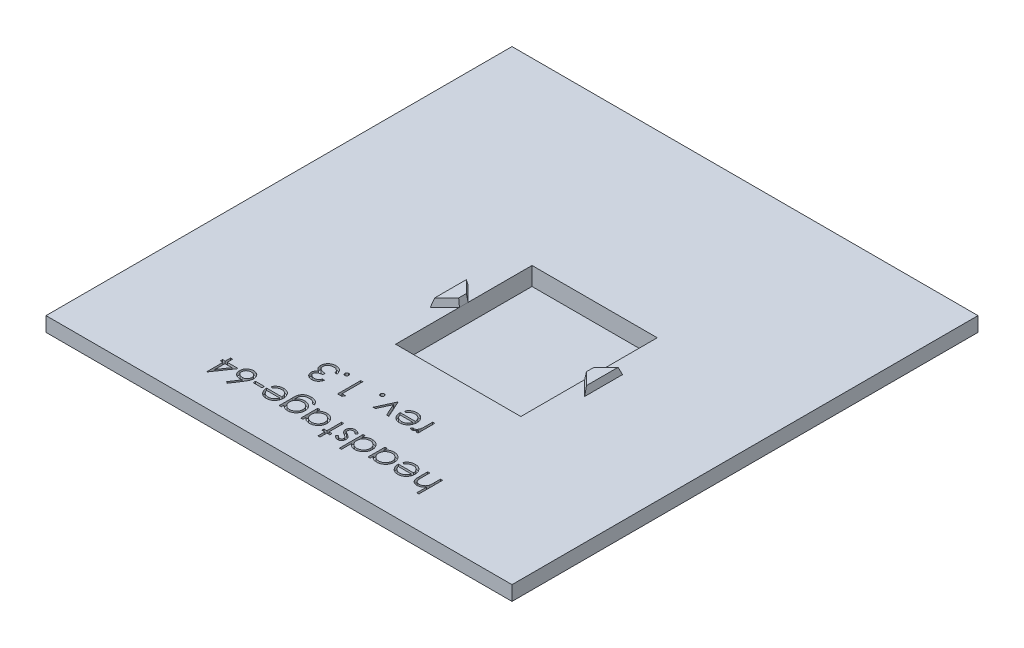
SolidWorks part; units mm, degrees
ref_plane "Front Plane" through (0, 0, 0) normal (0, 0, 1) x (1, 0, 0)
ref_plane "Top Plane" through (0, 0, 0) normal (0, 1, 0) x (1, 0, 0)
ref_plane "Right Plane" through (0, 0, 0) normal (1, 0, 0) x (0, 0, -1)
sketch "Sketch1" plane through (0, 0, 0) normal (0, 1, 0) x (1, 0, 0)
  line L1 (-32, 32) -> (32, 32)
  line L2 (-32, 32) -> (-32, -32)
  line L3 (-32, -32) -> (32, -32)
  line L4 (32, 32) -> (32, -32)
  line L5 (-32, 32) -> (32, -32) construction
  line L6 (-32, -32) -> (32, 32) construction
  point P0 (0, 0)
  dimension "D1" = 64
  dimension "D2" = 64
extrude "Boss-Extrude1" add sketch "Sketch1" along normal blind 4 contours L2 L3 L4 L1
sketch "Sketch2" plane through (0, 0, 0) normal (0, -1, 0) x (1, 0, 0)
  line L1 (-30, 30) -> (30, 30)
  line L2 (-30, 30) -> (-30, -30)
  line L3 (-30, -30) -> (30, -30)
  line L4 (30, 30) -> (30, -30)
  line L5 (-30, 30) -> (30, -30) construction
  line L6 (-30, -30) -> (30, 30) construction
  line L7 (32, 32) -> (-32, 32)
  line L8 (32, 32) -> (32, -32)
  line L9 (32, -32) -> (-32, -32)
  line L10 (-32, 32) -> (-32, -32)
  line L11 (32, 32) -> (-32, -32) construction
  line L12 (32, -32) -> (-32, 32) construction
  point P0 (0, 0)
  point P6 (0, 0)
  line M5 (-32, -32) -> (32, -32)
  line M6 (32, -32) -> (32, 32)
  line M7 (32, 32) -> (-32, 32)
  line M8 (-32, 32) -> (-32, -32)
  dimension "D1" = 2
  dimension "D2" = 2
extrude "Cut-Extrude1" cut sketch "Sketch2" against normal blind 2 contours L1 L4 L3 L2 M8 M5 M6 M7
sketch "Sketch6" plane through (0, 4, 0) normal (0, 1, 0) x (1, 0, 0)
  line L0 (12.61, -2.63) -> (13.4068, -3.4268) construction
  line L4 (12.61, -1.43) -> (12.61, -2.63) construction
  line L5 (12.61, -1.43) -> (13.4068, -0.6332) construction
  line L6 (-4.59, -1.43) -> (-5.3868, -0.6332) construction
  line L7 (-4.59, -2.63) -> (-4.59, -1.43) construction
  line L8 (-4.59, -2.63) -> (-5.3868, -3.4268) construction
  arc A0 (13.4068, -0.6332) -> (-5.3868, -0.6332) centre (4.01, -2.03) ccw construction
  arc A1 (-5.3868, -3.4268) -> (13.4068, -3.4268) centre (4.01, -2.03) ccw construction
  point P4 (12.61, -2.03)
  point P14 (4.01, -2.03)
  dimension "D4" = 19
  dimension "D1" = 4.01
  dimension "D2" = 2.03
  dimension "D3" = 8.6
  dimension "D5" = 1.2
  dimension "D6" = 2
sketch "Sketch7" plane through (0, 4, 0) normal (0, 1, 0) x (1, 0, 0)
  line L5 (12.61, -1.43) -> (12.61, -2.63) construction
  line L6 (12.61, 7.3375) -> (-4.59, 7.3375)
  line L14 (12.61, 7.3375) -> (12.61, -11.3975)
  line L15 (12.61, -11.3975) -> (-4.59, -11.3975)
  line L16 (-4.59, 7.3375) -> (-4.59, -11.3975)
  line L17 (12.61, 7.3375) -> (-4.59, -11.3975) construction
  line L18 (12.61, -11.3975) -> (-4.59, 7.3375) construction
  point P0 (4.01, -2.03)
extrude "Cut-Extrude2" cut sketch "Sketch7" against normal blind 2.5
sketch "Sketch8" plane through (0, 4, 0) normal (0, 1, 0) x (1, 0, 0)
  line L0 (12.61, -2.63) -> (14.61, -4.63)
  line L1 (14.61, -4.63) -> (14.61, -0.3574)
  line L2 (12.61, -2.63) -> (12.61, -1.43)
  line L3 (12.61, -1.43) -> (14.61, 0.57)
  line L4 (14.61, 0.57) -> (14.61, -0.3574)
  line L5 (12.61, -1.43) -> (13.4068, -0.6332) construction
  dimension "D1" = 2
extrude "Boss-Extrude2" add sketch "Sketch8" along normal blind 1 draft 10
ref_plane "Plane1" through (4.01, 0, 0) normal (-1, 0, 0) x (0, 0, 1)
mirror "Mirror1" about plane through (4.01, 0, 0) normal (-1, 0, 0) of "Boss-Extrude2"
sketch "Sketch9" plane through (0, 4, 0) normal (0, 1, 0) x (1, 0, 0)
  line L0 (22.252, -24.3686) -> (-21.8745, -24.3686) construction
  text T0 "headstage-64\r\nrev. 1.3"
extrude "Cut-Extrude3" cut sketch "Sketch9" against normal blind 0.5
